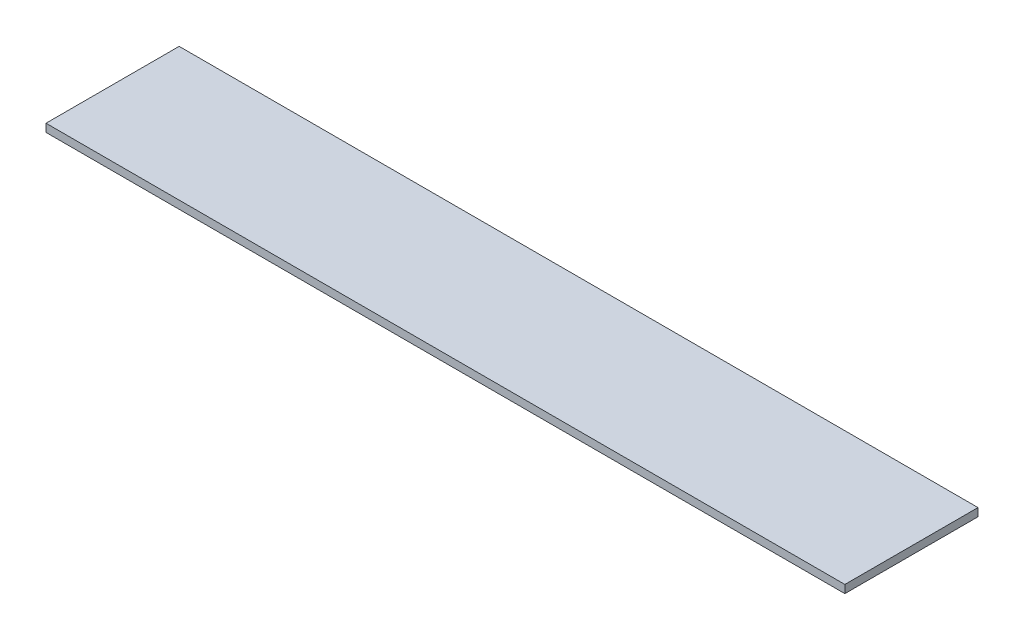
SolidWorks part; units mm, degrees
material "A-玻璃纤维"
ref_plane "前视基准面" through (0, 0, 0) normal (0, 0, 1) x (1, 0, 0)
ref_plane "上视基准面" through (0, 0, 0) normal (0, 1, 0) x (1, 0, 0)
ref_plane "右视基准面" through (0, 0, 0) normal (1, 0, 0) x (0, 0, -1)
sketch "草图1" plane through (0, 0, 0) normal (0, 1, 0) x (1, 0, 0)
  line L1 (-150, 25) -> (150, 25)
  line L2 (-150, 25) -> (-150, -25)
  line L3 (-150, -25) -> (150, -25)
  line L4 (150, 25) -> (150, -25)
  line L5 (-150, 25) -> (150, -25) construction
  line L6 (-150, -25) -> (150, 25) construction
  point P0 (0, 0)
  dimension "D1" = 300
  dimension "D2" = 50
extrude "凸台-拉伸1" add sketch "草图1" along normal blind 3
